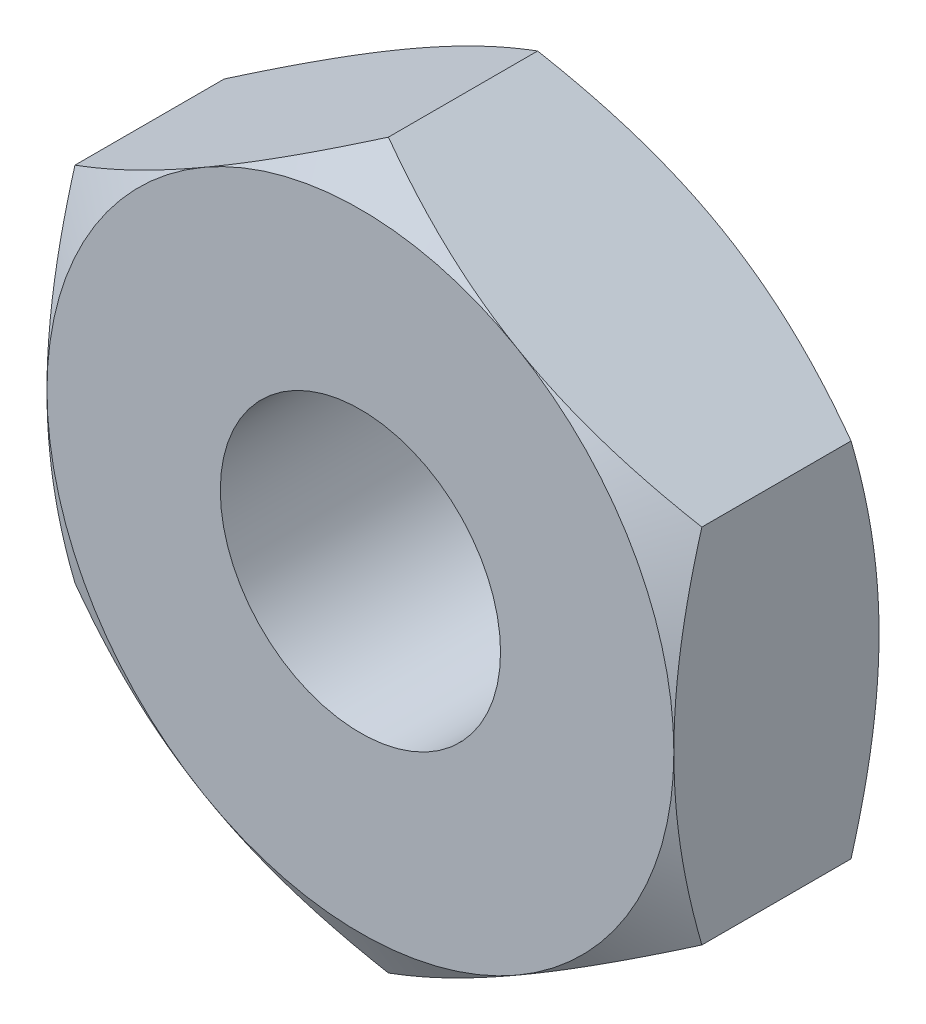
SolidWorks part; units mm, degrees
ref_plane "基准面1" through (0, 0, 0) normal (0, 0, 1) x (1, 0, 0)
ref_plane "基准面2" through (0, 0, 0) normal (0, 1, 0) x (1, 0, 0)
ref_plane "基准面3" through (0, 0, 0) normal (1, 0, 0) x (0, 0, -1)
sketch "尺寸草图" plane through (0, 0, 0) normal (0, 0, 1) x (1, 0, 0)
  line L0 (0, 0) -> (6, 0) construction
  line L1 (0, 0) -> (12, 0) construction
  line L2 (6, 0) -> (10.6, 0) construction
  line L3 (-2.8571, 0) -> (0, 0) construction
  point P3 (3, 0)
  point P4 (0.5, 0)
  point P5 (6, 0)
  point P6 (1.8, 0)
  point P8 (5.5, 0)
  dimension "D1" = 2.8571
  dimension "D" = 3
  dimension "P" = 0.5
  dimension "e(最小)" = 6
  dimension "m(最大)" = 1.8
  dimension "s(公称)" = 5.5
  dimension "dw(最小)" = 4.6
sketch "草图1" plane through (0, 0, 0) normal (0, 0, 1) x (1, 0, 0)
  line L0 (-2.75, 0) -> (2.75, 0) construction
  line L1 (0, 3.1754) -> (0, -3.1754) construction
  line L3 (0, 3.1754) -> (-2.75, 1.5877)
  line L4 (-2.75, 1.5877) -> (-2.75, -1.5877)
  line L5 (-2.75, -1.5877) -> (0, -3.1754)
  line L6 (0, -3.1754) -> (2.75, -1.5877)
  line L7 (2.75, -1.5877) -> (2.75, 1.5877)
  line L8 (2.75, 1.5877) -> (0, 3.1754)
  circle A0 centre (0, 0) radius 2.75 construction
  circle A1 centre (0, 0) radius 1.2294
  point P2 (0, 2.8246)
  dimension "D1" = 6
  dimension "D" = 2.4588
  dimension "D2" = 5.5
extrude "基体-拉伸" add sketch "草图1" along normal blind 1.8
cosmetic thread "装饰螺纹线1" parameters "D2"=3
sketch "草图2" plane through (0, 0, 0) normal (0, 0, -1) x (-1, 0, 0)
  circle A0 centre (0, 0) radius 2.75
  circle A1 centre (0, 0) radius 1.2294 construction
  dimension "s" = 5.5
extrude "切除-拉伸1" cut sketch "草图2" against normal through all draft 60 flip side to cut
sketch "草图3" plane through (0, 0, 1.8) normal (0, 0, 1) x (1, 0, 0)
  circle A0 centre (0, 0) radius 2.75
  dimension "D1" = 5.5
extrude "切除-拉伸2" cut sketch "草图3" against normal through all draft 60 flip side to cut
